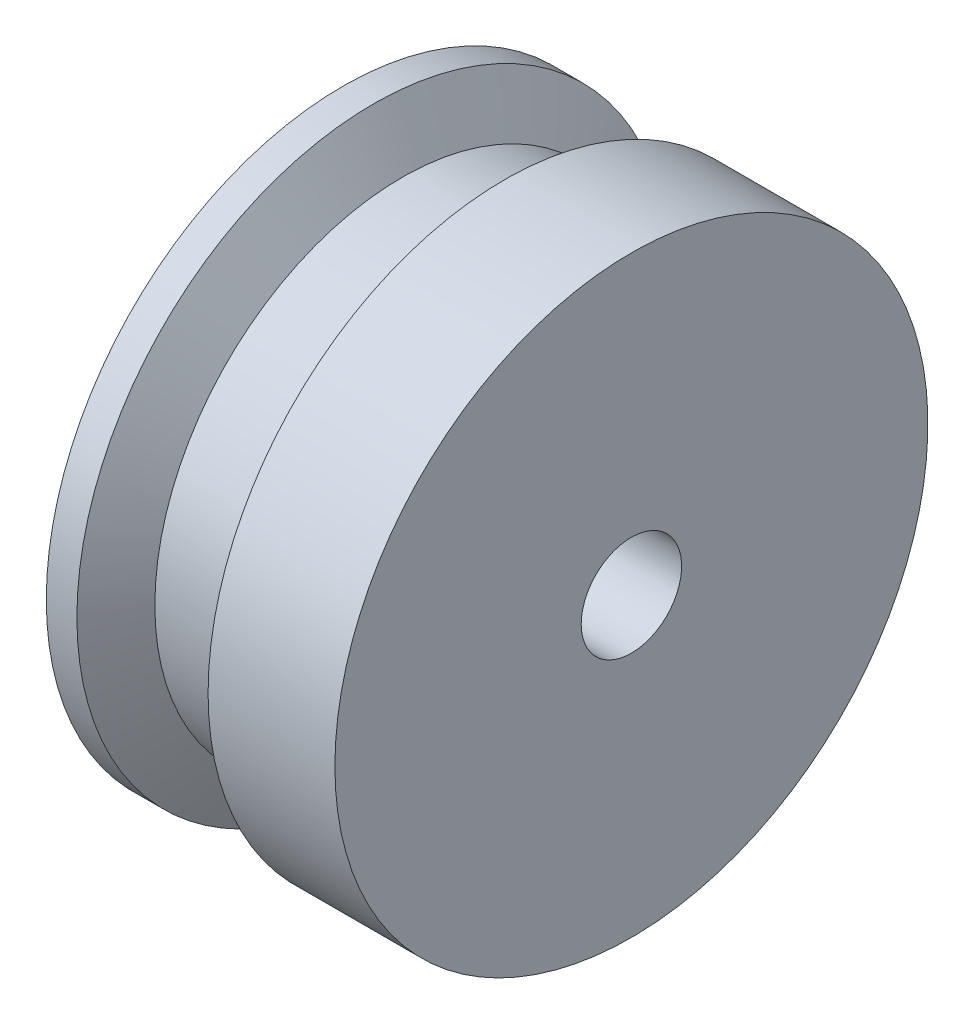
SolidWorks part; units mm, degrees
material "ABS"
ref_plane "Front Plane" through (0, 0, 0) normal (0, 0, 1) x (1, 0, 0)
ref_plane "Top Plane" through (0, 0, 0) normal (0, 1, 0) x (1, 0, 0)
ref_plane "Right Plane" through (0, 0, 0) normal (1, 0, 0) x (0, 0, -1)
sketch "Sketch1" plane through (0, 0, 0) normal (0, 0, 1) x (1, 0, 0)
  line L0 (0, 3.2258) -> (18.542, 3.2258)
  line L1 (18.542, 3.2258) -> (18.542, 19.05)
  line L2 (18.542, 19.05) -> (10.395, 19.05)
  line L3 (10.395, 19.05) -> (8.5619, 15.875)
  line L4 (8.5619, 15.875) -> (3.7994, 15.875)
  line L5 (3.7994, 15.875) -> (1.9663, 19.05)
  line L6 (1.9663, 19.05) -> (0, 19.05)
  line L7 (0, 19.05) -> (0, 3.2258)
  line L8 (0, 7.5027) -> (6.1807, 7.5027) construction
  line L9 (6.1807, 7.5027) -> (12.3613, 7.5027) construction
  line L10 (12.3613, 7.5027) -> (18.542, 7.5027) construction
  line L11 (0, 0) -> (12.8416, 0) construction
  point P2 (6.1807, 15.875)
  dimension "D1" = 3.2258
  dimension "D2" = 18.542
  dimension "D3" = 4.7625
  dimension "D4" = 60
  dimension "D5" = 19.05
  dimension "D6" = 15.875
revolve "Revolve1" add sketch "Sketch1" angle 360 about L11
